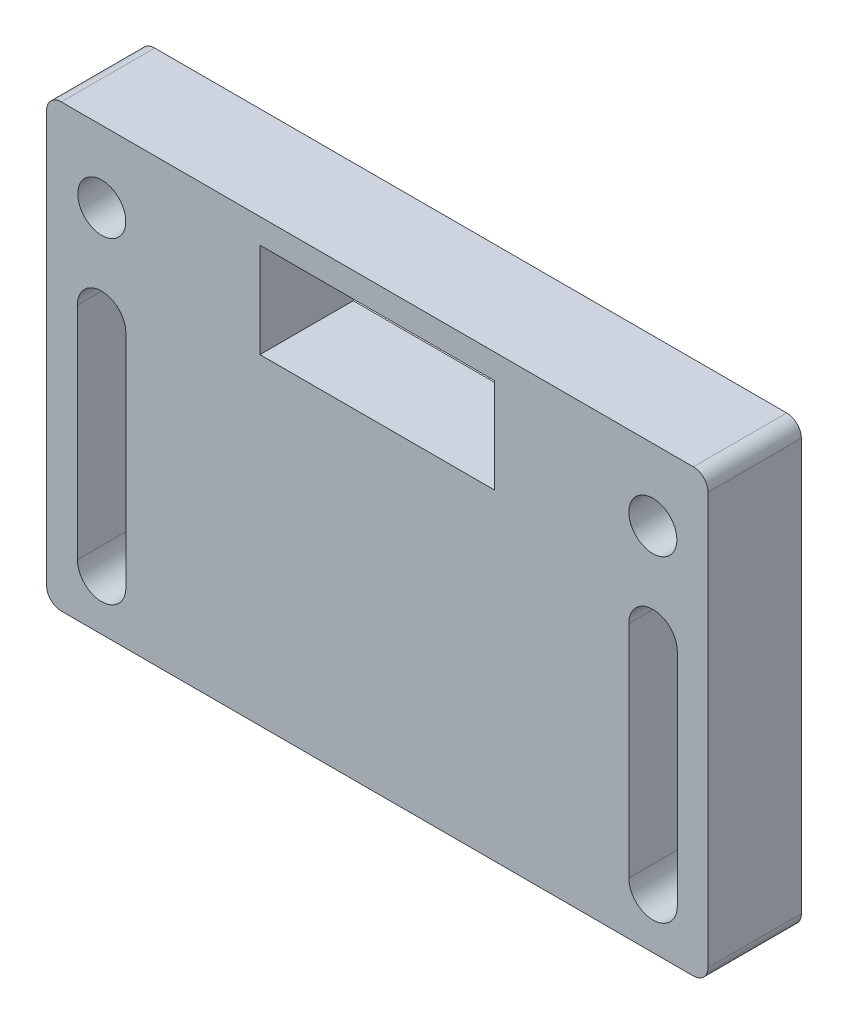
SolidWorks part; units mm, degrees
ref_plane "Front Plane" through (0, 0, 0) normal (0, 0, 1) x (1, 0, 0)
ref_plane "Top Plane" through (0, 0, 0) normal (0, 1, 0) x (1, 0, 0)
ref_plane "Right Plane" through (0, 0, 0) normal (1, 0, 0) x (0, 0, -1)
sketch "Sketch1" plane through (0, 0, 0) normal (0, 0, 1) x (1, 0, 0)
  line L0 (45, 0) -> (45, -60) construction
  line L1 (0, 0) -> (90, 0)
  line L2 (0, 0) -> (0, -60)
  line L3 (0, -60) -> (90, -60)
  line L4 (90, 0) -> (90, -60)
  line L5 (29.025, -3.3671) -> (29.025, -16.2671)
  line L6 (29.025, -16.2671) -> (60.975, -16.2671)
  line L7 (60.975, -16.2671) -> (60.975, -3.3671)
  line L9 (60.975, -3.3671) -> (45, -3.3671)
  line L10 (45, -3.3671) -> (29.025, -3.3671)
  dimension "D1" = 90
  dimension "D2" = 60
  dimension "D3" = 31.95
  dimension "D4" = 12.9
extrude "Boss-Extrude1" add sketch "Sketch1" along normal blind 12.7
sketch "Sketch2" plane through (0, 0, 0) normal (0, 0, -1) x (-1, 0, 0)
  line L0 (-82.49, -9.7171) -> (-7.51, -9.7171) construction
  line L1 (0, -9.7171) -> (-7.51, -9.7171)
  line L2 (-90, -60) -> (-90, 0) construction
  line L3 (-90, -9.7171) -> (-82.49, -9.7171)
  line L4 (0, 0) -> (0, -60) construction
  dimension "D1" = 7.51
  dimension "D2" = 7.51
  dimension "D3" = 74.98
hole_wizard "CSK for 1/4 Flat Head Machine Screw1" positions "Sketch3" profile "Sketch4" countersink size "1/4" standard "ANSI Inch" end condition through all
sketch "Sketch3" plane through (0, 0, 0) normal (0, 0, -1) x (-1, 0, 0)
  point P0 (-82.49, -9.7171)
  point P3 (-7.51, -9.7171)
sketch "Sketch4" plane through (82.49, -9.7171, 0) normal (1, 0, 0) x (0, 1, 0)
  line L0 (0, 0) -> (0, 12.7)
  line L1 (0, 12.7) -> (3.2639, 12.7)
  line L2 (3.2639, 12.7) -> (3.2639, 3.6524)
  line L3 (3.2639, 3.6524) -> (6.4389, 0)
  line L5 (6.4389, 0) -> (0, 0)
  line L6 (-3.2639, 3.6524) -> (-6.4389, 0) construction
  line L11 (0, -6.35) -> (0, 107.95) construction
  dimension "Thru Hole Dia." = 6.5278
  dimension "Thru Hole Depth" = 12.7
  dimension "Near C'Sink Dia." = 12.8778
  dimension "Near C'Sink Angle" = 82
fillet "Fillet1" radius 2 4 edges at (0, -60, 6.35) (0, 0, 6.35) (90, 0, 6.35) (90, -60, 6.35)
sketch "Sketch5" plane through (0, 0, 0) normal (0, 0, -1) x (-1, 0, 0)
  line L0 (-10.785, -22.8474) -> (-10.785, -52.8474)
  line L1 (-4.185, -52.8474) -> (-4.185, -22.8474)
  line L2 (-10.785, -52.8474) -> (-79.215, -52.8474) construction
  line L3 (-79.215, -52.8474) -> (-79.215, -22.8474)
  line L4 (-85.815, -52.8474) -> (-85.815, -22.8474)
  line L5 (-85.815, -37.8474) -> (-90, -37.8474) construction
  line L6 (-2, -60) -> (-88, -60) construction
  line L7 (-90, -58) -> (-90, -2) construction
  line L8 (-4.185, -37.8474) -> (0, -37.8474) construction
  line L9 (-45, -46.606) -> (-45, 0) construction
  line L10 (-88, 0) -> (-2, 0) construction
  line L13 (0, -2) -> (0, -58) construction
  arc A0 (-10.785, -52.8474) -> (-4.185, -52.8474) centre (-7.485, -52.8474) ccw
  arc A1 (-4.185, -22.8474) -> (-10.785, -22.8474) centre (-7.485, -22.8474) ccw
  arc A2 (-85.815, -52.8474) -> (-79.215, -52.8474) centre (-82.515, -52.8474) ccw
  arc A3 (-79.215, -22.8474) -> (-85.815, -22.8474) centre (-82.515, -22.8474) ccw
  point P24 (0, -37.8474)
  point P27 (0, -37.8474)
  dimension "D1" = 3.3
  dimension "D4" = 3.3
  dimension "D7" = 7.1526
  dimension "D2" = 30
  dimension "D3" = 68.43
  dimension "D5" = 30
extrude "Cut-Extrude1" cut sketch "Sketch5" against normal through all
